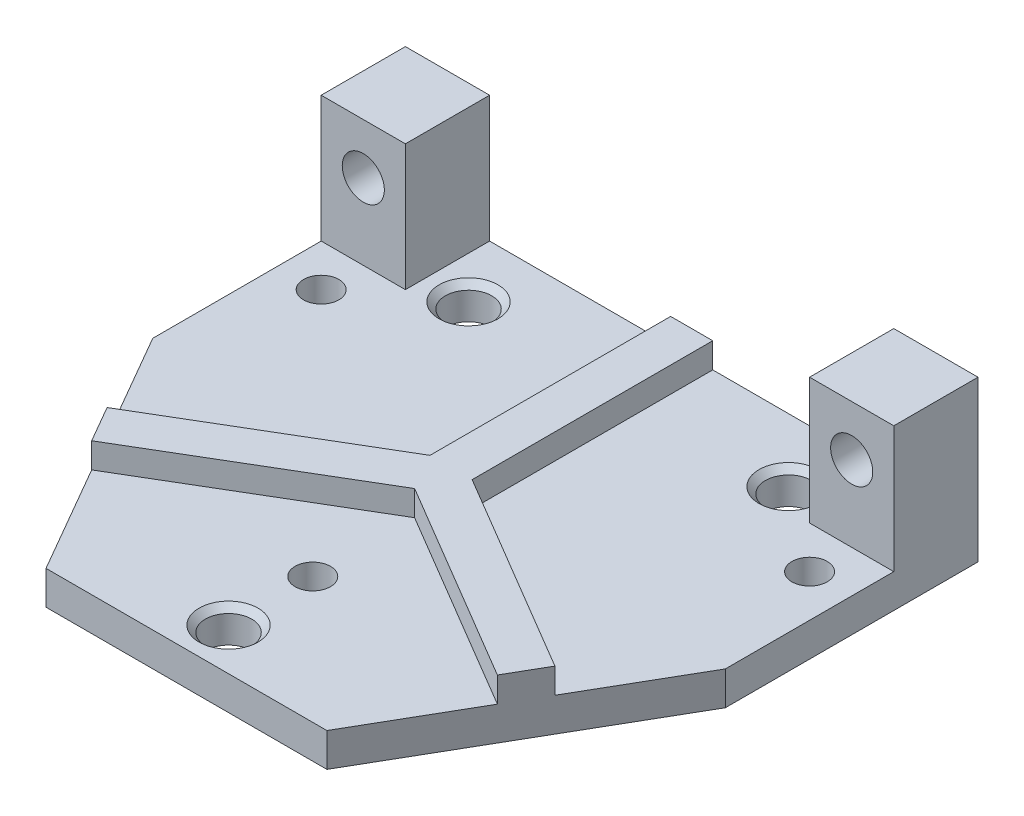
SolidWorks part; units mm, degrees
material "PET"
ref_plane "Front Plane" through (0, 0, 0) normal (0, 0, 1) x (1, 0, 0)
ref_plane "Top Plane" through (0, 0, 0) normal (0, 1, 0) x (1, 0, 0)
ref_plane "Right Plane" through (0, 0, 0) normal (1, 0, 0) x (0, 0, -1)
sketch "Sketch1" plane through (0, 0, 0) normal (0, 1, 0) x (1, 0, 0)
  line L0 (-30, 15) -> (30, 15) construction
  line L1 (-16.6795, -30) -> (16.6795, -30)
  line L2 (-34, 0) -> (-34, 30)
  line L3 (-34, 30) -> (34, 30)
  line L4 (34, 0) -> (34, 30)
  line L5 (-22.5251, -19.8751) -> (34, 30) construction
  line L6 (-34, 30) -> (22.5251, -19.8751) construction
  line L7 (-34, 22.5) -> (34, 22.5) construction
  line L8 (-34, -25) -> (34, -25) construction
  line L9 (-34, 0) -> (-16.6795, -30)
  line L10 (16.6795, -30) -> (34, 0)
  line L11 (0, -30) -> (0, -15) construction
  line L12 (0, -25) -> (0, -15) construction
  line L13 (-34, 0) -> (34, 0) construction
  circle A0 centre (-19, 22.5) radius 2.75
  circle A1 centre (19, 22.5) radius 2.75
  circle A2 centre (0, -25) radius 2.75
  circle A3 centre (-29, 15) radius 2.1
  circle A4 centre (29, 15) radius 2.1
  circle A5 centre (0, -15) radius 2.1
  point P0 (0, 0)
  dimension "D5" = 5.5
  dimension "D6" = 5.5
  dimension "D7" = 5.5
  dimension "D8" = 4.2
  dimension "D9" = 4.2
  dimension "D10" = 5
  dimension "D11" = 5
  dimension "D13" = 4.2
  dimension "D14" = 15
  dimension "D21" = 15
  dimension "D2" = 68
  dimension "D3" = 47.5
  dimension "D4" = 7.5
  dimension "D12" = 15
  dimension "D15" = 120
  dimension "D16" = 120
  dimension "D17" = 30
  dimension "D18" = 34
  dimension "D19" = 60
  dimension "D20" = 15
extrude "Boss-Extrude1" add sketch "Sketch1" along normal blind 4
sketch "Sketch2" plane through (0, 4, 0) normal (0, 1, 0) x (1, 0, 0)
  line L0 (-25.3397, -15) -> (0, 0) construction
  line L1 (-34, 0) -> (-16.6795, -30) construction
  line L2 (0, 0) -> (0, 30) construction
  line L3 (34, 30) -> (-34, 30) construction
  line L4 (0, 0) -> (25.3397, -15) construction
  line L5 (16.6795, -30) -> (34, 0) construction
  line L6 (-24.0663, -17.1513) -> (0, -2.9052) construction
  line L7 (-26.6132, -12.8487) -> (-2.5, 1.4253) construction
  line L8 (-26.5898, -12.8348) -> (-24.0897, -17.1652)
  line L9 (0, -2.9052) -> (24.0663, -17.1513) construction
  line L10 (2.5, 1.4253) -> (26.6132, -12.8487) construction
  line L11 (24.0897, -17.1652) -> (26.5898, -12.8348)
  line L12 (-26.5898, -12.8348) -> (-2.5, 1.4253)
  line L13 (-2.5, 1.4253) -> (-2.5, 30)
  line L14 (2.5, 1.4253) -> (26.5898, -12.8348)
  line L15 (2.5, 1.4253) -> (2.5, 30)
  line L16 (-24.0897, -17.1652) -> (0, -2.9052)
  line L17 (0, -2.9052) -> (24.0897, -17.1652)
  line L18 (-2.5, 30) -> (2.5, 30)
  dimension "D1" = 2.5
  dimension "D2" = 2.5
  dimension "D3" = 2.5
extrude "Boss-Extrude2" add sketch "Sketch2" along normal blind 3
sketch "Sketch3" plane through (0, 4, 0) normal (0, 1, 0) x (1, 0, 0)
  line L1 (-34, 30) -> (-24, 30)
  line L2 (-34, 30) -> (-34, 20)
  line L3 (-34, 20) -> (-24, 20)
  line L4 (-24, 30) -> (-24, 20)
  line L5 (34, 30) -> (24, 30)
  line L6 (34, 30) -> (34, 20)
  line L7 (34, 20) -> (24, 20)
  line L8 (24, 30) -> (24, 20)
  dimension "D1" = 10
  dimension "D2" = 10
  dimension "D3" = 10
extrude "Boss-Extrude3" add sketch "Sketch3" along normal blind 15
sketch "Sketch4" plane through (0, 0, -30) normal (0, 0, -1) x (-1, 0, 0)
  line L0 (-24, 19) -> (-34, 7) construction
  line L1 (24, 19) -> (34, 19) construction
  line L2 (24, 19) -> (34, 7) construction
  line L4 (-34, 19) -> (-24, 19) construction
  line L5 (-34, 19) -> (-34, 0) construction
  line L6 (34, 19) -> (34, 0) construction
  circle A0 centre (-29, 13) radius 2.5
  circle A1 centre (29, 13) radius 2.5
  dimension "D3" = 5
  dimension "D4" = 5
  dimension "D5" = 6
  dimension "D1" = 6
extrude "Cut-Extrude1" cut sketch "Sketch4" against normal through all
chamfer "Chamfer1" distance 0.75 angle 45 3 edges at (0, 4, 27.75) (-19, 4, -19.75) (19, 4, -19.75)
